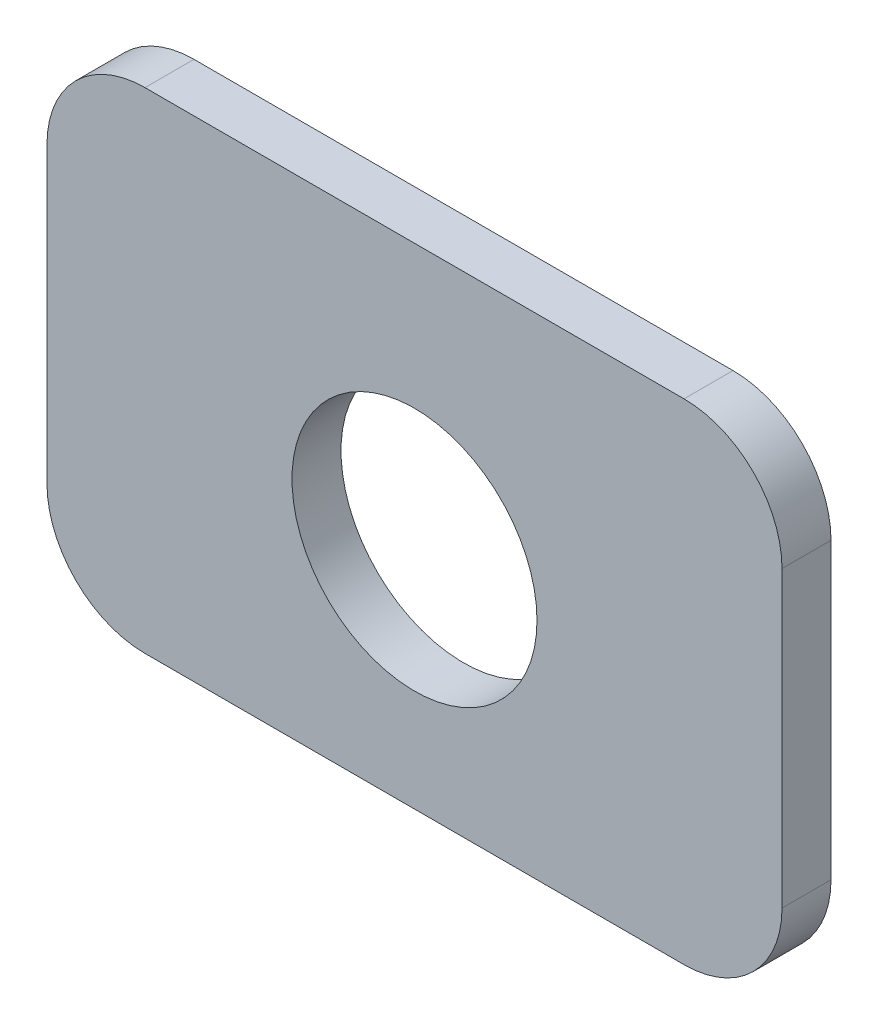
SolidWorks part; units mm, degrees
ref_plane "Front Plane" through (0, 0, 0) normal (0, 0, 1) x (1, 0, 0)
ref_plane "Top Plane" through (0, 0, 0) normal (0, 1, 0) x (1, 0, 0)
ref_plane "Right Plane" through (0, 0, 0) normal (1, 0, 0) x (0, 0, -1)
sketch "Sketch1" plane through (0, 0, 0) normal (0, 0, 1) x (1, 0, 0)
  line L1 (-5.5, 5) -> (5.5, 5)
  line L2 (-7.5, 3) -> (-7.5, -3)
  line L3 (-5.5, -5) -> (5.5, -5)
  line L4 (7.5, 3) -> (7.5, -3)
  line L5 (-7.5, 5) -> (7.5, -5) construction
  line L6 (-7.5, -5) -> (7.5, 5) construction
  circle A0 centre (0, -0.416) radius 2.5
  arc A1 (5.5, 5) -> (7.5, 3) centre (5.5, 3) cw
  arc A2 (5.5, -5) -> (7.5, -3) centre (5.5, -3) ccw
  arc A3 (-7.5, -3) -> (-5.5, -5) centre (-5.5, -3) ccw
  arc A4 (-5.5, 5) -> (-7.5, 3) centre (-5.5, 3) ccw
  point P0 (0, 0)
  dimension "D3" = 5
  dimension "D4" = 2
  dimension "D1" = 15
  dimension "D2" = 10
extrude "Boss-Extrude1" add sketch "Sketch1" along normal blind 1
